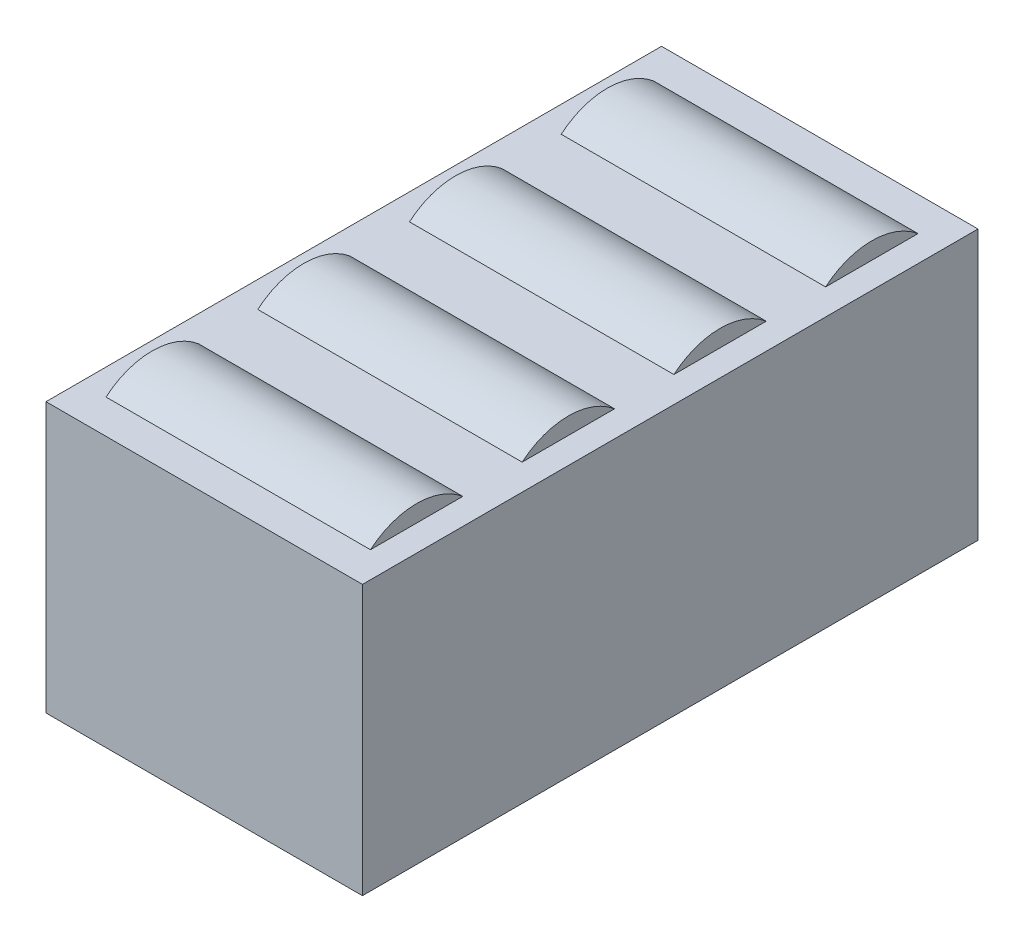
SolidWorks part; units mm, degrees
ref_plane "Plan de face" through (0, 0, 0) normal (0, 0, 1) x (1, 0, 0)
ref_plane "Plan de dessus" through (0, 0, 0) normal (0, 1, 0) x (1, 0, 0)
ref_plane "Plan de droite" through (0, 0, 0) normal (1, 0, 0) x (0, 0, -1)
sketch "Esquisse1" plane through (0, 0, 0) normal (0, 0, 1) x (1, 0, 0)
  line L1 (0, 0) -> (73, 0)
  line L2 (0, 0) -> (0, 62.2)
  line L3 (0, 62.2) -> (73, 62.2)
  line L4 (73, 0) -> (73, 62.2)
  dimension "D1" = 73
  dimension "D2" = 62.2
extrude "Boss.-Extru.1" add sketch "Esquisse1" along normal blind 142
sketch "Esquisse2" plane through (73, 0, 0) normal (1, 0, 0) x (0, 0, -1)
  line L0 (-142, 31.1) -> (0, 31.1) construction
  line L1 (-142, 0) -> (-142, 62.2) construction
  line L2 (0, 0) -> (0, 62.2) construction
  line L3 (26.5459, 49.6) -> (-181.4138, 49.6) construction
  line L4 (-181.4138, 12.6) -> (35.8248, 12.6) construction
  line L5 (35.8248, 12.6) -> (35.8248, 25.4396) construction
  line L6 (-71, 62.2) -> (-71, 0) construction
  line L7 (-142, 62.2) -> (0, 62.2) construction
  line L8 (-142, 0) -> (0, 0) construction
  line L9 (-88.5, 62.2) -> (-88.5, 0) construction
  line L10 (-123.5, 0) -> (-123.5, 62.2) construction
  line L11 (-53.5, 62.2) -> (-53.5, 0) construction
  line L12 (-18.5, 0) -> (-18.5, 62.2) construction
  circle A0 centre (-123.5, 49.6) radius 16.5
  circle A1 centre (-88.5, 49.6) radius 16.5
  circle A2 centre (-53.5, 49.6) radius 16.5
  circle A3 centre (-18.5, 49.6) radius 16.5
  circle A4 centre (-123.5, 12.6) radius 16.5
  circle A5 centre (-88.5, 12.6) radius 16.5
  circle A6 centre (-53.5, 12.6) radius 16.5
  circle A7 centre (-18.5, 12.6) radius 16.5
  dimension "D5" = 33
  dimension "D1" = 37
  dimension "D2" = 35
  dimension "D3" = 35
  dimension "D4" = 35
extrude "Boss.-Extru.2" add sketch "Esquisse2" against normal offset from surface (61 mm away) 6 from offset 6 up to face at (0, 31.1, 71)
